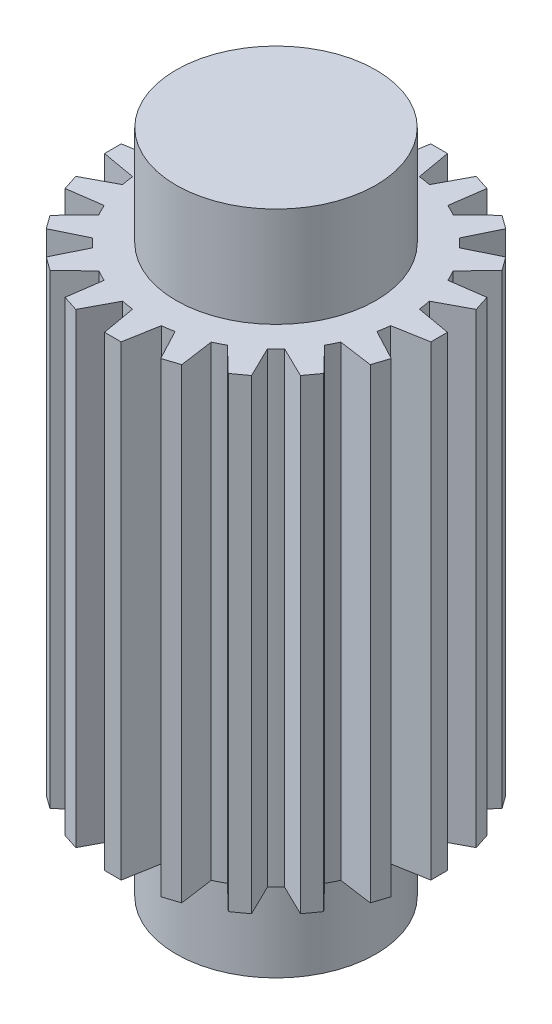
SolidWorks part; units mm, degrees
ref_plane "Front Plane" through (0, 0, 0) normal (0, 0, 1) x (1, 0, 0)
ref_plane "Top Plane" through (0, 0, 0) normal (0, 1, 0) x (1, 0, 0)
ref_plane "Right Plane" through (0, 0, 0) normal (1, 0, 0) x (0, 0, -1)
sketch "Sketch1" plane through (0, 0, 0) normal (0, 1, 0) x (1, 0, 0)
  circle A0 centre (0, 0) radius 3.9
  dimension "D1" = 7.8
extrude "Boss-Extrude1" add sketch "Sketch1" along normal blind 14
sketch "Sketch2" plane through (0, 14, 0) normal (0, 1, 0) x (1, 0, 0)
  line L0 (0, 3.9) -> (0, 4.9) construction
  line L1 (-0.25, 4.9) -> (0.25, 4.9)
  line L2 (-0.25, 4.9) -> (-0.6401, 2.6874)
  line L3 (-0.6401, 2.6874) -> (0.6401, 2.6874)
  line L4 (0.6401, 2.6874) -> (0.25, 4.9)
  line L5 (0, 3.9) -> (0, 2.6874) construction
  circle A0 centre (0, 0) radius 3.9 construction
  point P9 (0, 4.9)
  dimension "D1" = 0.5
  dimension "D2" = 100
  dimension "D3" = 1
extrude "Boss-Extrude2" add sketch "Sketch2" against normal blind 14
pattern_circular "CirPattern1" count 20 over 360 about axis through (0, 0, 0) along (0, 1, 0) of "Boss-Extrude2"
sketch "Sketch3" plane through (0, 14, 0) normal (0, 1, 0) x (1, 0, 0)
  circle A0 centre (0, 0) radius 4.25
  dimension "D1" = 8.5
sketch "Sketch5" plane through (0, 14, 0) normal (0, 1, 0) x (1, 0, 0)
  circle A0 centre (0, 0) radius 3
  dimension "D1" = 6
extrude "Boss-Extrude3" add sketch "Sketch5" along normal blind 3 and the other way blind 17
sketch "Sketch6" plane through (0, 0, 0) normal (0, -1, 0) x (1, 0, 0)
  circle A0 centre (0, 0) radius 4.0676
